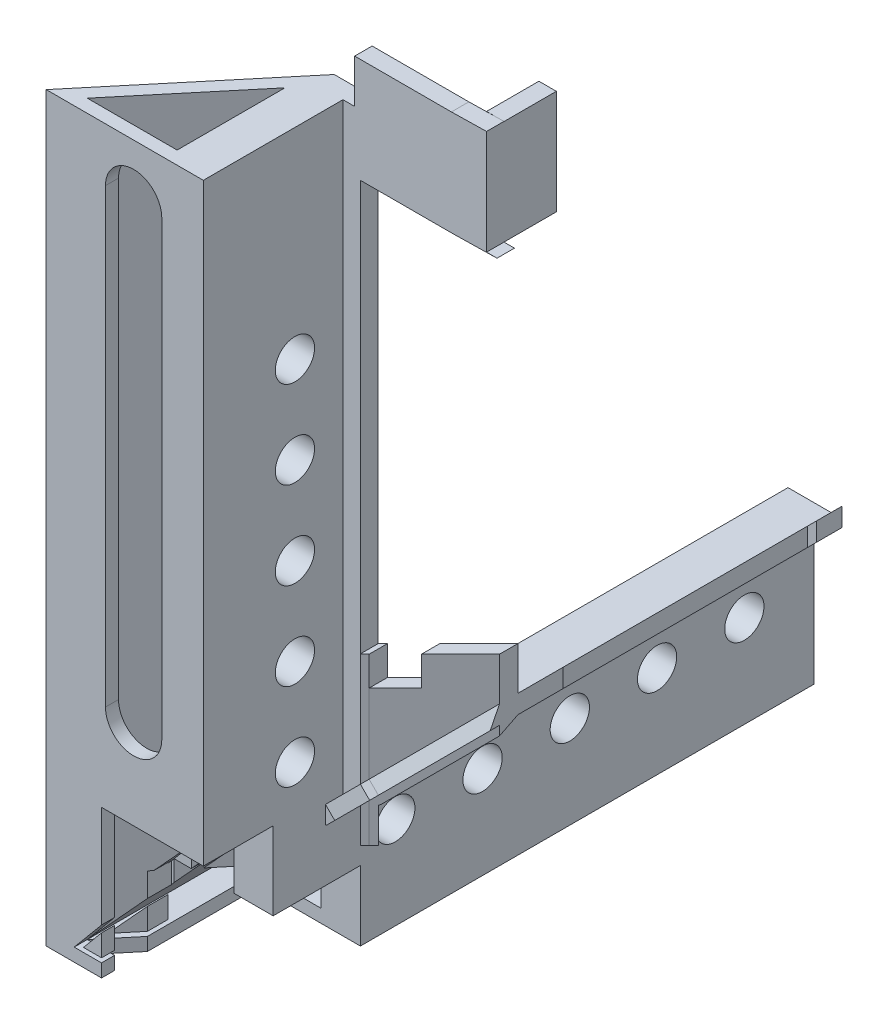
SolidWorks part; units mm, degrees
ref_plane "前视基准面" through (0, 0, 0) normal (0, 0, 1) x (1, 0, 0)
ref_plane "上视基准面" through (0, 0, 0) normal (0, 1, 0) x (1, 0, 0)
ref_plane "右视基准面" through (0, 0, 0) normal (1, 0, 0) x (0, 0, -1)
other "Configuration Table"
sketch "草图1" plane through (0, 0, 0) normal (1, 0, 0) x (0, 0, -1)
  line L0 (0, 70) -> (0, 0)
  line L3 (18, 18) -> (70, 18)
  line L4 (70, 0) -> (70, 18)
  line L7 (0, 70) -> (18, 70)
  line L8 (18, 18) -> (18, 70)
  line L10 (0, 0) -> (70, 0)
  dimension "D1" = 70
  dimension "D2" = 70
  dimension "D3" = 18
  dimension "D4" = 18
  dimension "D5" = 52
extrude "凸台-拉伸5" add sketch "草图1" along normal blind 3
sketch "草图5" plane through (0, 0, -70) normal (0, 0, -1) x (-1, 0, 0)
  line L0 (0, 0) -> (15, 0)
  line L1 (15, 0) -> (0, 18)
  line L2 (0, 18) -> (0, 0)
  line L3 (10.7299, 2) -> (2, 12.4759)
  line L4 (2, 12.4759) -> (2, 2)
  line L5 (2, 2) -> (10.7299, 2)
  dimension "D1" = 15
  dimension "D2" = 2
extrude "凸台-拉伸6" add sketch "草图5" against normal blind 70
sketch "草图6" plane through (0, 70, 0) normal (0, 1, 0) x (1, 0, 0)
  line L0 (0, 0) -> (-15, 0)
  line L1 (-15, 0) -> (0, 18)
  line L2 (0, 18) -> (0, 0)
  line L8 (-10.7299, 2) -> (-2, 12.4759)
  line L9 (-2, 12.4759) -> (-2, 2)
  line L10 (-2, 2) -> (-10.7299, 2)
  dimension "D1" = 2
extrude "凸台-拉伸7" add sketch "草图6" against normal blind 70
sketch "草图7" plane through (0, 0, 0) normal (0, 0, 1) x (1, 0, 0)
  line L1 (3, 0) -> (-8.665, 0)
  line L2 (3, 0) -> (3, 16.939)
  line L3 (3, 16.939) -> (-8.665, 16.939)
  line L4 (-8.665, 0) -> (-8.665, 16.939)
extrude "切除-拉伸1" cut sketch "草图7" against normal blind 3
sketch "草图8" plane through (0, 0, 0) normal (0, -1, 0) x (1, 0, 0)
  line L0 (-8.665, -2) -> (-8.665, 0) construction
  line L1 (3, -3) -> (-8.665, -3)
  line L2 (3, -3) -> (3, -18)
  line L3 (3, -18) -> (-8.665, -18)
  line L4 (-8.665, -3) -> (-8.665, -18)
  dimension "D1" = 15
extrude "切除-拉伸2" cut sketch "草图8" against normal blind 3
sketch "草图9" plane through (0, 3, 0) normal (0, -1, 0) x (1, 0, 0)
  line L8 (-2, -18) -> (3, -18)
  line L9 (3, -18) -> (3, -3)
  line L10 (3, -3) -> (-2, -3)
  line L11 (-2, -3) -> (-2, -12.4759)
  line L12 (-2, -12.4759) -> (-8.665, -4.4779)
  line L13 (-8.665, -4.4779) -> (-8.665, -7.602)
  line L14 (-8.665, -7.602) -> (-2, -15.6)
  line L15 (-2, -15.6) -> (-2, -18)
  line L16 (-2, -18) -> (3, -18)
  line L17 (3, -18) -> (3, -3)
  line L18 (3, -3) -> (-2, -3)
  line L19 (-2, -3) -> (-2, -12.4759)
  line L20 (-2, -12.4759) -> (-8.665, -4.4779)
  line L21 (-8.665, -4.4779) -> (-8.665, -7.602)
  line L22 (-8.665, -7.602) -> (-2, -15.6)
  line L23 (-2, -15.6) -> (-2, -18)
  dimension "D1" = 0
extrude "切除-拉伸3" cut sketch "草图9" against normal blind 5
sketch "草图10" plane through (0, 0, -3) normal (0, 0, 1) x (1, 0, 0)
  line L8 (-2, 12.4759) -> (-2, 8)
  line L9 (-2, 8) -> (3, 8)
  line L10 (3, 8) -> (3, 16.939)
  line L11 (3, 16.939) -> (-2, 16.939)
  line L12 (-2, 16.939) -> (-2, 15.6)
  line L13 (-2, 15.6) -> (-8.665, 7.602)
  line L14 (-8.665, 7.602) -> (-8.665, 4.4779)
  line L15 (-8.665, 4.4779) -> (-2, 12.4759)
  line L16 (-2, 12.4759) -> (-2, 8)
  line L17 (-2, 8) -> (3, 8)
  line L18 (3, 8) -> (3, 16.939)
  line L19 (3, 16.939) -> (-2, 16.939)
  line L20 (-2, 16.939) -> (-2, 15.6)
  line L21 (-2, 15.6) -> (-8.665, 7.602)
  line L22 (-8.665, 7.602) -> (-8.665, 4.4779)
  line L23 (-8.665, 4.4779) -> (-2, 12.4759)
  dimension "D1" = 0
extrude "切除-拉伸4" cut sketch "草图10" against normal blind 5
sketch "草图11" plane through (3, 0, 0) normal (1, 0, 0) x (0, 0, -1)
  line L1 (18, 70) -> (16, 70)
  line L2 (18, 70) -> (18, 18)
  line L4 (16, 70) -> (16, 16)
  line L5 (70, 18) -> (18, 18)
  line L6 (70, 18) -> (70, 16)
  line L7 (70, 16) -> (16, 16)
  dimension "D1" = 2
  dimension "D2" = 2
extrude "凸台-拉伸8" add sketch "草图11" along normal blind 2
sketch "草图12" plane through (0, 0, -70) normal (0, 0, -1) x (-1, 0, 0)
  line L0 (-39.4697, 52.5303) -> (-38.9988, 49.9382)
  line L2 (-5.1575, 16.0969) -> (-38.9988, 49.9382)
  line L3 (-5, 18.0607) -> (-39.4697, 52.5303)
  line L4 (-5.1575, 16.0969) -> (-5, 16)
  line L5 (-5, 16) -> (-5, 18.0607)
  dimension "D1" = 47.8588
  dimension "D2" = 48.7475
  dimension "D3" = 33.8413
  dimension "D4" = 18.0607
extrude "凸台-拉伸9" add sketch "草图12" against normal blind 93
sketch "草图13" plane through (0, 70, 0) normal (0, 1, 0) x (1, 0, 0)
  line L3 (5.5303, 16.4697) -> (40.5303, 51.4697)
  line L4 (4.4697, 17.5303) -> (38.6129, 51.6736)
  line L5 (5.5303, 16.4697) -> (5, 16)
  line L6 (5, 16) -> (5, 18.3391)
  line L7 (5, 70) -> (5, 18) construction
  line L8 (40.5303, 51.4697) -> (38.6129, 51.6736)
  line M7 (5, 16) -> (5, 18)
extrude "凸台-拉伸10" add sketch "草图13" against normal blind 93 contours L3 L8 L4 L6 L5 M7
sketch "草图14" plane through (-6.5303, 6.5303, 0) normal (-0.7071, 0.7071, 0) x (0, 0, 1)
  line L5 (-50.409, 65.0538) -> (-16.4697, 17.0563)
  line L6 (-16.4697, 17.0563) -> (-16, 16.3063)
  line L7 (-16, 16.3063) -> (23, 16.3063)
  line L8 (23, 16.3063) -> (23, 65.0538)
  line L9 (23, 65.0538) -> (-50.409, 65.0538)
  line L10 (-50.409, 65.0538) -> (-16.4697, 17.0563)
  line L11 (-16.4697, 17.0563) -> (-16, 16.3063)
  line L12 (-16, 16.3063) -> (23, 16.3063)
  line L13 (23, 16.3063) -> (23, 65.0538)
  line L14 (23, 65.0538) -> (-50.409, 65.0538)
  dimension "D1" = 0
extrude "切除-拉伸6" cut sketch "草图14" against normal blind 93
sketch "草图16" plane through (-6.5303, 0, -6.5303) normal (-0.7071, 0, -0.7071) x (-0.7071, 0, 0.7071)
  line L5 (-16.5291, 16.0969) -> (-63.8422, 49.5523)
  line L6 (-63.8422, 49.5523) -> (-63.8422, -23)
  line L7 (-63.8422, -23) -> (-16.3063, -23)
  line L8 (-16.3063, -23) -> (-16.3063, 16)
  line L9 (-16.3063, 16) -> (-16.5291, 16.0969)
  line L10 (-16.5291, 16.0969) -> (-63.8422, 49.5523)
  line L11 (-63.8422, 49.5523) -> (-63.8422, -23)
  line L12 (-63.8422, -23) -> (-16.3063, -23)
  line L13 (-16.3063, -23) -> (-16.3063, 16)
  line L14 (-16.3063, 16) -> (-16.5291, 16.0969)
  dimension "D1" = 0
extrude "切除-拉伸10" cut sketch "草图16" against normal blind 93
sketch "草图17" plane through (0, -23, 0) normal (0, -1, 0) x (1, 0, 0)
  line L3 (40.5303, -51.4697) -> (39.6736, -50.6129)
  line L4 (39.6736, -50.6129) -> (38.6129, -51.6736)
  line L5 (38.6129, -51.6736) -> (40.5303, -51.4697)
  line L6 (40.5303, -51.4697) -> (39.6736, -50.6129)
  line L7 (39.6736, -50.6129) -> (38.6129, -51.6736)
  line L8 (38.6129, -51.6736) -> (40.5303, -51.4697)
  dimension "D1" = 0
extrude "切除-拉伸11" cut sketch "草图17" against normal blind 93
sketch "草图18" plane through (0, -23, 0) normal (0, -1, 0) x (1, 0, 0)
  line L4 (5, -16) -> (5, -18.0607)
  line L5 (5, -18.0607) -> (6.0607, -17)
  line L6 (6.0607, -17) -> (5.5303, -16.4697)
  line L7 (5.5303, -16.4697) -> (5, -16)
  line L8 (5, -16) -> (5, -18.0607)
  line L9 (5, -18.0607) -> (6.0607, -17)
  line L10 (6.0607, -17) -> (5.5303, -16.4697)
  line L11 (5.5303, -16.4697) -> (5, -16)
  dimension "D1" = 0
extrude "切除-拉伸16" cut sketch "草图18" against normal blind 35
sketch "草图19" plane through (0, 0, 23) normal (0, 0, 1) x (1, 0, 0)
  line L4 (6.0607, 17) -> (5, 18.0607)
  line L5 (5, 18.0607) -> (5, 16)
  line L6 (5, 16) -> (5.1575, 16.0969)
  line L7 (5.1575, 16.0969) -> (6.0607, 17)
  line L8 (6.0607, 17) -> (5, 18.0607)
  line L9 (5, 18.0607) -> (5, 16)
  line L10 (5, 16) -> (5.1575, 16.0969)
  line L11 (5.1575, 16.0969) -> (6.0607, 17)
  dimension "D1" = 0
extrude "切除-拉伸17" cut sketch "草图19" against normal blind 35
sketch "草图20" plane through (3, 0, 0) normal (1, 0, 0) x (0, 0, -1)
  line L0 (16, 70) -> (16, 16) construction
  line L1 (16, 70) -> (0, 70) construction
  line L2 (70, 0) -> (70, 16) construction
  line L3 (18.2182, 16.0969) -> (70, 16.0969) construction
  circle A0 centre (10.5, 62) radius 2.25
  circle A1 centre (10.5, 52) radius 2.25
  circle A2 centre (10.5, 42) radius 2.25
  circle A3 centre (10.5, 32) radius 2.25
  circle A4 centre (10.5, 22) radius 2.25
  circle A6 centre (62, 10.5969) radius 2.25
  circle A7 centre (52, 10.5969) radius 2.25
  circle A8 centre (42, 10.5969) radius 2.25
  circle A9 centre (32, 10.5969) radius 2.25
  circle A10 centre (22, 10.5969) radius 2.25
  dimension "D1" = 5.5
  dimension "D2" = 4.5
  dimension "D8" = 8
  dimension "D10" = 4.5
  dimension "D3" = 10
  dimension "D4" = 8
  dimension "D5" = 10
  dimension "D6" = 10
  dimension "D7" = 10
  dimension "D9" = 5.5
  dimension "D11" = 5
extrude "切除-拉伸18" cut sketch "草图20" against normal blind 6
sketch "草图22" plane through (0, 16, 0) normal (0, -1, 0) x (1, 0, 0)
  line L0 (5.1575, -18.2182) -> (5.1575, -70) construction
  line L1 (5.1575, -67.1011) -> (7.6575, -67.1011)
  line L2 (5.1575, -67.1011) -> (5.1575, -27.1011)
  line L3 (5.1575, -27.1011) -> (7.6575, -27.1011)
  line L4 (7.6575, -67.1011) -> (7.6575, -27.1011)
  dimension "D1" = 2.5
  dimension "D2" = 40
extrude "切除-拉伸22" cut sketch "草图22" against normal blind 6
sketch "草图23" plane through (0, 0, -16) normal (0, 0, 1) x (1, 0, 0)
  line L0 (5.5303, 18.591) -> (5.5303, 70) construction
  line L1 (5.5303, 67.0123) -> (8.5303, 67.0123)
  line L2 (5.5303, 67.0123) -> (5.5303, 27.6367)
  line L3 (5.5303, 27.6367) -> (8.5303, 27.6367)
  line L4 (8.5303, 67.0123) -> (8.5303, 27.6367)
  dimension "D1" = 3
extrude "切除-拉伸23" cut sketch "草图23" against normal blind 6
sketch "草图24" plane through (0, 0, 0) normal (0, 0, 1) x (1, 0, 0)
  line L0 (39.6736, 70) -> (39.6736, 49.5523) construction
  line L1 (56.6372, 76.7751) -> (14.6736, 76.7751)
  line L2 (56.6372, 76.7751) -> (56.6372, 6.5143)
  line L3 (56.6372, 6.5143) -> (14.6736, 6.5143)
  line L4 (14.6736, 76.7751) -> (14.6736, 6.5143)
  dimension "D1" = 25
extrude "切除-拉伸24" cut sketch "草图24" against normal through all
sketch "草图25" plane through (0, 0, 0) normal (0, -1, 0) x (1, 0, 0)
  line L0 (13, -15.5995) -> (13, -70)
  line L1 (3, -18) -> (3, -70) construction
  line L3 (14.6736, -70) -> (13, -70)
  line L4 (14.6736, -70) -> (14.6736, -15.5995)
  line L5 (14.6736, -15.5995) -> (13, -15.5995)
  line L6 (13, -70) -> (13, -15.5995)
  dimension "D1" = 10
extrude "切除-拉伸25" cut sketch "草图25" against normal through all contours L4 L5 L0 L3
sketch "草图26" plane through (0, 0, 0) normal (0, -1, 0) x (1, 0, 0)
  line L1 (17.2161, -72.7671) -> (6.1625, -72.7671)
  line L2 (17.2161, -72.7671) -> (17.2161, -31.2323)
  line L3 (17.2161, -31.2323) -> (6.1625, -31.2323)
  line L4 (6.1625, -72.7671) -> (6.1625, -31.2323)
extrude "切除-拉伸26" cut sketch "草图26" against normal through all
sketch "草图27" plane through (0, 70, 0) normal (0, 1, 0) x (1, 0, 0)
  line L0 (5, 18.0607) -> (5, 12.7163)
  line L2 (5, 12) -> (5, 16) construction
  line L10 (5.5303, 16.4697) -> (13, 23.9393)
  line L11 (13, 23.9393) -> (13, 26.0607)
  line L12 (13, 26.0607) -> (5, 18.0607)
  line L13 (5, 18.0607) -> (5, 18)
  line L14 (5, 18) -> (0, 18)
  line L15 (0, 18) -> (-15, 0)
  line L16 (-15, 0) -> (3, 0)
  line L17 (3, 0) -> (3, 16)
  line L18 (3, 16) -> (5, 16)
  line L19 (5, 16) -> (5.5303, 16.4697)
  line L20 (5.5303, 16.4697) -> (13, 23.9393)
  line L21 (13, 23.9393) -> (13, 26.0607)
  line L22 (13, 26.0607) -> (5, 18.0607)
  line L23 (5, 18.0607) -> (5, 18)
  line L29 (5, 16) -> (5.5303, 16.4697)
  line M12 (5.5303, 16.4697) -> (13, 23.9393)
  line M13 (13, 23.9393) -> (13, 26.0607)
  line M14 (13, 26.0607) -> (5, 18.0607)
  line M15 (5, 18.0607) -> (5, 18)
  line M21 (5, 16) -> (5.5303, 16.4697)
  dimension "D1" = 0
extrude "切除-拉伸27" cut sketch "草图27" against normal blind 39 contours L0 M15 M21 M12 M13 M14
sketch "草图28" plane through (0, 70, 0) normal (0, 1, 0) x (1, 0, 0)
  line L6 (3, 16) -> (5, 16)
  line L7 (5, 16) -> (5, 18)
  line L8 (5, 18) -> (0, 18)
  line L9 (0, 18) -> (-15, 0)
  line L10 (-15, 0) -> (3, 0)
  line L11 (3, 0) -> (3, 16)
  line L12 (3, 16) -> (5, 16)
  line L13 (5, 16) -> (5, 18)
  line L14 (5, 18) -> (0, 18)
  line L15 (0, 18) -> (-15, 0)
  line L16 (-15, 0) -> (3, 0)
  line L17 (3, 0) -> (3, 16)
  dimension "D1" = 0
extrude "凸台-拉伸11" add sketch "草图28" along normal blind 15
ref_plane "基准面1" through (0, 75, 0) normal (0, 1, 0) x (1, 0, 0)
sketch "草图30" plane through (0, 75, 0) normal (0, 1, 0) x (1, 0, 0)
  line L0 (5, 16) -> (16.8407, 16)
  line L1 (18.6575, 18) -> (18.6575, 81)
  line L2 (18.6575, 81) -> (20.6575, 81)
  line L3 (20.6575, 81) -> (20.6575, 16)
  line L4 (20.6575, 16) -> (16.8407, 16)
  line L5 (5, 18) -> (18.6575, 18)
  line L6 (5, 16) -> (5, 18)
  line L7 (5.1575, 67.1011) -> (5.1575, 27.1011) construction
  dimension "D1" = 65
  dimension "D2" = 2
  dimension "D3" = 13.5
extrude "凸台-拉伸13" add sketch "草图30" along normal blind 3 and the other way blind 3
chamfer "倒角1" distance 3 angle 45 1 edges at (18.6575, 75, -18)
chamfer "倒角2" distance 5 angle 45 2 edges at (5, 72, -17) (5, 78, -17)
sketch "草图31" plane through (0, 0, -81) normal (0, 0, -1) x (-1, 0, 0)
  line L1 (-15.6575, 72) -> (-26.6214, 72)
  line L2 (-15.6575, 72) -> (-15.6575, 81.3994)
  line L3 (-15.6575, 81.3994) -> (-26.6214, 81.3994)
  line L4 (-26.6214, 72) -> (-26.6214, 81.3994)
extrude "切除-拉伸28" cut sketch "草图31" against normal through all
sketch "草图32" plane through (0, 0, -18) normal (0, 0, -1) x (-1, 0, 0)
  line L0 (-15.4289, 90) -> (-4.3448, 90)
  line L3 (-15.6575, 78) -> (-15.4289, 90)
  line L4 (-4.3448, 90) -> (-4.3448, 85)
  line L5 (-5, 85) -> (0, 85) construction
  line L6 (-15.6575, 78) -> (-10, 78) construction
  line L7 (-5, 85) -> (-5, 83) construction
  line L8 (-5, 83) -> (-10, 78) construction
  line L9 (-15.6575, 78) -> (-10, 78)
  line L10 (-5, 85) -> (-5, 83)
  line L11 (-5, 85) -> (-4.3448, 85)
  line L12 (-5, 83) -> (-10, 78)
  line L13 (-5, 16) -> (-3, 16) construction
  dimension "D1" = 74
extrude "凸台-拉伸15" add sketch "草图32" against normal blind 2
sketch "草图34" plane through (0, 0, -18) normal (0, 0, -1) x (-1, 0, 0)
  line L1 (-15.4289, 90) -> (-13.4289, 90)
  line L2 (-15.4289, 90) -> (-15.4289, 87)
  line L3 (-15.4289, 87) -> (-13.4289, 87)
  line L4 (-13.4289, 90) -> (-13.4289, 87)
  dimension "D1" = 2
  dimension "D2" = 3
extrude "凸台-拉伸16" add sketch "草图34" along normal blind 102
chamfer "倒角3" distance 3 angle 45 1 edges at (13.4289, 88.5, -18)
sketch "草图35" plane through (0, 90, 0) normal (0, 1, 0) x (1, 0, 0)
  line L1 (10.4289, 18) -> (62.0319, 18)
  line L2 (10.4289, 18) -> (10.4289, 140.2921)
  line L3 (10.4289, 140.2921) -> (62.0319, 140.2921)
  line L4 (62.0319, 18) -> (62.0319, 140.2921)
extrude "切除-拉伸29" cut sketch "草图35" against normal blind 10
sketch "草图36" plane through (0, 90, 0) normal (0, 1, 0) x (1, 0, 0)
  line L4 (15.4289, 16) -> (15.4289, 18)
  line L5 (15.4289, 18) -> (4.3448, 18)
  line L6 (4.3448, 18) -> (4.3448, 16)
  line L7 (4.3448, 16) -> (15.4289, 16)
  line L8 (15.4289, 16) -> (15.4289, 18)
  line L9 (15.4289, 18) -> (4.3448, 18)
  line L10 (4.3448, 18) -> (4.3448, 16)
  line L11 (4.3448, 16) -> (15.4289, 16)
  dimension "D1" = 0
extrude "凸台-拉伸17" add sketch "草图36" along normal blind 7
sketch "草图37" plane through (0, 0, -18) normal (0, 0, -1) x (-1, 0, 0)
  line L1 (-15.4289, 97) -> (-13.4289, 97)
  line L2 (-15.4289, 97) -> (-15.4289, 95)
  line L3 (-15.4289, 95) -> (-13.4289, 95)
  line L4 (-13.4289, 97) -> (-13.4289, 95)
  dimension "D1" = 2
  dimension "D2" = 2
extrude "凸台-拉伸18" add sketch "草图37" along normal blind 83
chamfer "倒角4" distance 3 angle 45 1 edges at (13.4289, 96, -18)
chamfer "倒角5" distance 2 angle 45 1 edges at (12.9289, 95, -18)
sketch "草图38" plane through (0, 97, 0) normal (0, 1, 0) x (1, 0, 0)
  line L0 (15.4289, 16) -> (15.4289, 18) construction
  line L1 (13.4289, 101) -> (15.4289, 101)
  line L2 (13.4289, 101) -> (13.4289, 18)
  line L3 (13.4289, 18) -> (15.4289, 18)
  line L4 (15.4289, 101) -> (15.4289, 18)
  line L5 (15.4289, 16) -> (15.4289, 101) construction
extrude "切除-拉伸30" cut sketch "草图38" against normal blind 83
sketch "草图39" plane through (0, 97, 0) normal (0, 1, 0) x (1, 0, 0)
  line L0 (13.4289, 18) -> (10.4289, 18)
  line L7 (13.4289, 18) -> (13.4289, 21)
  line L8 (13.4289, 21) -> (10.4289, 18)
  line L9 (10.4289, 18) -> (4.3448, 18)
  line L10 (4.3448, 18) -> (4.3448, 16)
  line L11 (4.3448, 16) -> (15.4289, 16)
  line L12 (15.4289, 16) -> (15.4289, 18)
  line L13 (15.4289, 18) -> (13.4289, 18)
  line L14 (13.4289, 18) -> (13.4289, 21)
  line L15 (13.4289, 21) -> (10.4289, 18)
  line L17 (4.3448, 18) -> (4.3448, 16)
  line M8 (13.4289, 18) -> (13.4289, 21)
  line M9 (13.4289, 21) -> (10.4289, 18)
  dimension "D1" = 0
extrude "切除-拉伸31" cut sketch "草图39" against normal blind 83 contours L0 M8 M9
sketch "草图40" plane through (17.1375, 0.3265, 0) normal (0.9998, 0.0191, 0) x (0, 0, -1)
  line L4 (18, 77.6876) -> (18, 89.6897)
  line L5 (18, 89.6897) -> (16, 89.6897)
  line L6 (16, 89.6897) -> (16, 77.6876)
  line L7 (16, 77.6876) -> (18, 77.6876)
  line L8 (18, 77.6876) -> (18, 89.6897)
  line L9 (18, 89.6897) -> (16, 89.6897)
  line L10 (16, 89.6897) -> (16, 77.6876)
  line L11 (16, 77.6876) -> (18, 77.6876)
  dimension "D1" = 0
extrude "凸台-拉伸19" add sketch "草图40" along normal blind 5
sketch "草图41" plane through (0, 0, -18) normal (0, 0, -1) x (-1, 0, 0)
  line L0 (-20.428, 90.0953) -> (-15.4289, 90) construction
  line L1 (-20.6566, 78.0953) -> (-18.6566, 78.0953)
  line L2 (-20.6566, 78.0953) -> (-20.6566, 90.0615)
  line L3 (-20.6566, 90.0615) -> (-18.6566, 90.0615)
  line L4 (-18.6566, 78.0953) -> (-18.6566, 90.0615)
  dimension "D1" = 2
extrude "凸台-拉伸20" add sketch "草图41" along normal blind 6
sketch "草图42" plane through (0, 0, -18) normal (0, 0, -1) x (-1, 0, 0)
  line L1 (-4.3448, 97) -> (-15.4289, 97)
  line L2 (-4.3448, 97) -> (-4.3448, 90)
  line L3 (-4.3448, 90) -> (-15.4289, 90)
  line L4 (-15.4289, 97) -> (-15.4289, 90)
extrude "切除-拉伸32" cut sketch "草图42" against normal blind 6
sketch "草图43" plane through (0, 0, -18) normal (0, 0, -1) x (-1, 0, 0)
  line L1 (-5, 67) -> (-15.6575, 67)
  line L2 (-5, 67) -> (-5, 78)
  line L3 (-5, 78) -> (-15.6575, 78)
  line L4 (-15.6575, 67) -> (-15.6575, 78)
extrude "切除-拉伸33" cut sketch "草图43" against normal blind 6
sketch "草图44" plane through (0, 85, 0) normal (0, 1, 0) x (1, 0, 0)
  line L0 (0, 18) -> (0, 0)
  line L1 (-1.5, 13.8569) -> (-11.7974, 1.5)
  line L2 (-11.7974, 1.5) -> (-1.5, 1.5)
  line L3 (-1.5, 13.8569) -> (-1.5, 1.5)
  line L6 (3, 16) -> (4.3448, 16)
  line L7 (4.3448, 16) -> (4.3448, 18)
  line L8 (4.3448, 18) -> (0, 18)
  line L9 (0, 18) -> (-15, 0)
  line L10 (-15, 0) -> (3, 0)
  line L11 (3, 0) -> (3, 16)
  line L12 (3, 16) -> (4.3448, 16)
  line L15 (0, 18) -> (-15, 0)
  line L16 (-15, 0) -> (0, 0)
  dimension "D2" = 1.5
  dimension "D1" = 0
extrude "切除-拉伸34" cut sketch "草图44" against normal blind 98 contours L3 L1 L2
sketch "草图45" plane through (0, 0, -70) normal (0, 0, -1) x (-1, 0, 0)
  line L0 (2, 2) -> (10.7299, 2) construction
  line L1 (2, 12.4759) -> (2, 2) construction
  line L2 (10.7299, 2) -> (2, 12.4759) construction
  line L3 (2, 2) -> (10.7299, 2)
  line L4 (2, 12.4759) -> (2, 2)
  line L5 (10.7299, 2) -> (2, 12.4759)
  line L6 (11.7974, 1.5) -> (1.5, 13.8569)
  line L7 (1.5, 13.8569) -> (1.5, 1.5)
  line L8 (1.5, 1.5) -> (11.7974, 1.5)
  dimension "D1" = 0.5
extrude "切除-拉伸35" cut sketch "草图45" against normal blind 98
sketch "草图46" plane through (0, 0, 0) normal (0, 0, 1) x (1, 0, 0)
  line L0 (-4.9857, 78.8633) -> (-4.9857, 27.1144) construction
  line L1 (-1.7568, 78.8633) -> (-1.7568, 27.1144)
  line L2 (-8.2145, 78.8633) -> (-8.2145, 27.1144)
  arc A0 (-1.7568, 78.8633) -> (-8.2145, 78.8633) centre (-4.9857, 78.8633) ccw
  arc A1 (-8.2145, 27.1144) -> (-1.7568, 27.1144) centre (-4.9857, 27.1144) ccw
  point P2 (-4.9857, 52.9889)
extrude "切除-拉伸36" cut sketch "草图46" against normal blind 2
sketch "草图47" plane through (0, 0, 0) normal (0, -1, 0) x (1, 0, 0)
  line L0 (-5.6901, -25.7254) -> (-5.6901, -58.2768) construction
  line L1 (-2.6685, -25.7254) -> (-2.6685, -58.2768)
  line L2 (-8.7118, -25.7254) -> (-8.7118, -58.2768)
  arc A0 (-2.6685, -25.7254) -> (-8.7118, -25.7254) centre (-5.6901, -25.7254) ccw
  arc A1 (-8.7118, -58.2768) -> (-2.6685, -58.2768) centre (-5.6901, -58.2768) ccw
  point P2 (-5.6901, -42.0011)
extrude "切除-拉伸37" cut sketch "草图47" against normal blind 2
sketch "草图48" plane through (18.6566, 0, 0) normal (-1, 0, 0) x (0, 0, 1)
  line L4 (-18, 78.0953) -> (-18, 90.0615)
  line L5 (-18, 90.0615) -> (-24, 90.0615)
  line L6 (-24, 90.0615) -> (-24, 78.0953)
  line L7 (-24, 78.0953) -> (-18, 78.0953)
  line L8 (-18, 78.0953) -> (-18, 90.0615)
  line L9 (-18, 90.0615) -> (-24, 90.0615)
  line L10 (-24, 90.0615) -> (-24, 78.0953)
  line L11 (-24, 78.0953) -> (-18, 78.0953)
  dimension "D1" = 0
extrude "凸台-拉伸21" add sketch "草图48" along normal blind 1.2
sketch "草图49" plane through (20.6566, 0, 0) normal (1, 0, 0) x (0, 0, -1)
  line L1 (16, 90.0953) -> (24, 90.0953)
  line L2 (16, 90.0953) -> (16, 78.0953)
  line L3 (16, 78.0953) -> (24, 78.0953)
  line L4 (24, 90.0953) -> (24, 78.0953)
extrude "切除-拉伸38" cut sketch "草图49" against normal blind 1.2
